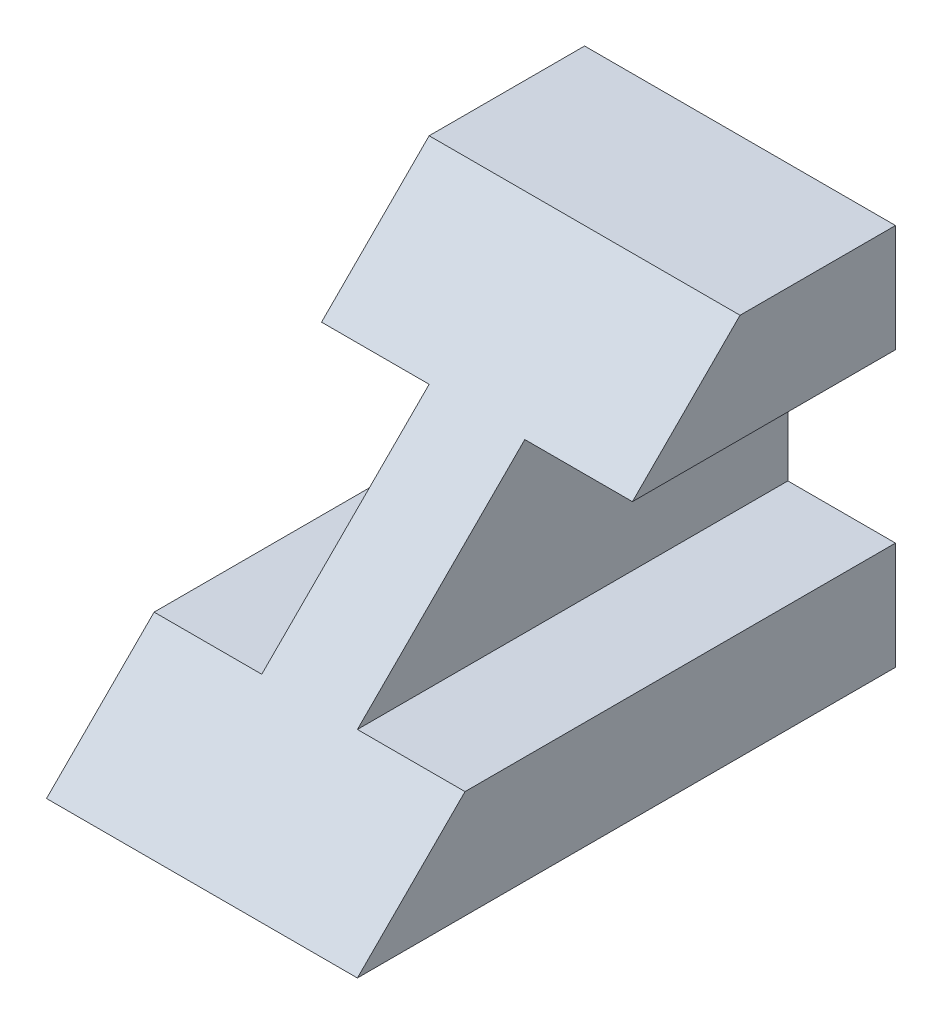
SolidWorks part; units mm, degrees
ref_plane "前视基准面" through (0, 0, 0) normal (0, 0, 1) x (1, 0, 0)
ref_plane "上视基准面" through (0, 0, 0) normal (0, 1, 0) x (1, 0, 0)
ref_plane "右视基准面" through (0, 0, 0) normal (1, 0, 0) x (0, 0, -1)
other "Configuration Table"
sketch "草图1" plane through (0, 0, 0) normal (1, 0, 0) x (0, 0, -1)
  line L0 (0, 0) -> (45, 0)
  line L1 (45, 0) -> (45, 32)
  line L2 (45, 32) -> (32, 32)
  line L3 (32, 32) -> (0, 0)
  dimension "D1" = 13
  dimension "D2" = 32
  dimension "D3" = 45
extrude "凸台-拉伸1" add sketch "草图1" along normal mid plane 26
sketch "草图2" plane through (0, 0, -45) normal (0, 0, -1) x (-1, 0, 0)
  line L0 (0, -1000) -> (0, 49000) construction
  line L1 (-13, 0) -> (-13, 32) construction
  line L2 (-13, 23) -> (-4, 23)
  line L3 (-13, 23) -> (-13, 9)
  line L4 (-13, 9) -> (-4, 9)
  line L5 (-4, 23) -> (-4, 9)
  line L6 (-13, 32) -> (13, 32) construction
  line L7 (-13, 0) -> (13, 0) construction
  line L8 (13, 9) -> (4, 9)
  line L9 (4, 23) -> (4, 9)
  line L10 (13, 23) -> (4, 23)
  line L11 (13, 23) -> (13, 9)
  dimension "D1" = 9
  dimension "D2" = 9
  dimension "D3" = 8
extrude "切除-拉伸1" cut sketch "草图2" against normal through all
